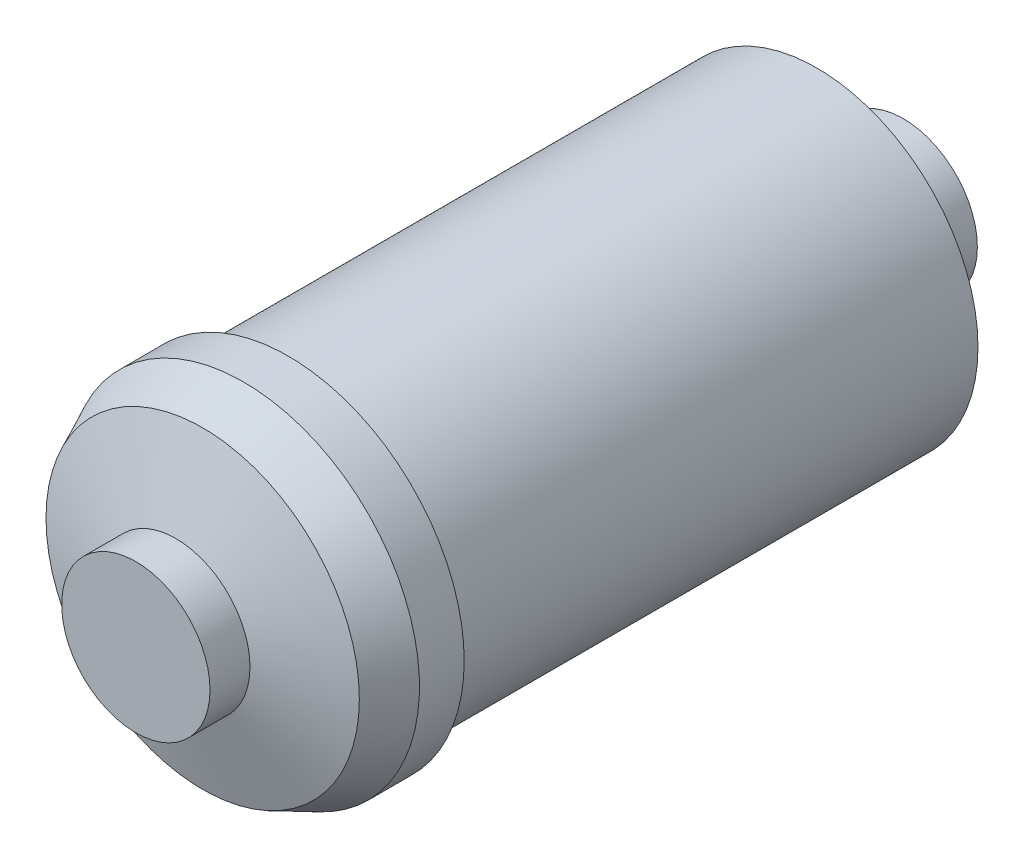
SolidWorks part; units mm, degrees
ref_plane "Front Plane" through (0, 0, 0) normal (0, 0, 1) x (1, 0, 0)
ref_plane "Top Plane" through (0, 0, 0) normal (0, 1, 0) x (1, 0, 0)
ref_plane "Right Plane" through (0, 0, 0) normal (1, 0, 0) x (0, 0, -1)
sketch "Sketch1" plane through (0, 0, 0) normal (0, 0, 1) x (1, 0, 0)
  circle A0 centre (0, 0) radius 14.732
  dimension "D1" = 29.464
extrude "Boss-Extrude1" add sketch "Sketch1" along normal blind 8.255
sketch "Sketch2" plane through (0, 0, 8.255) normal (0, 0, 1) x (1, 0, 0)
  circle A1 centre (0, 0) radius 14.732
  circle A2 centre (0, 0) radius 14.732
  dimension "D1" = 0
ref_plane "Plane1" through (0, 0, 17.145) normal (0, 0, 1) x (1, 0, 0)
sketch "Sketch3" plane through (0, 0, 17.145) normal (0, 0, 1) x (1, 0, 0)
  circle A0 centre (0, 0) radius 32.004
  dimension "D1" = 64.008
loft "Loft1" add profiles "Sketch2", "Sketch3"
sketch "Sketch4" plane through (0, 0, 17.145) normal (0, 0, 1) x (1, 0, 0)
  circle A1 centre (0, 0) radius 32.004
  circle A2 centre (0, 0) radius 32.004
  dimension "D1" = 0
extrude "Boss-Extrude2" add sketch "Sketch4" along normal blind 104.9655
sketch "Sketch5" plane through (0, 0, 122.1105) normal (0, 0, 1) x (1, 0, 0)
  circle A0 centre (0, 0) radius 34.925
  dimension "D1" = 69.85
extrude "Boss-Extrude3" add sketch "Sketch5" along normal blind 8.89
sketch "Sketch6" plane through (0, 0, 131.0005) normal (0, 0, 1) x (1, 0, 0)
  circle A1 centre (0, 0) radius 34.925
  circle A2 centre (0, 0) radius 34.925
  dimension "D1" = 0
ref_plane "Plane2" through (0, 0, 139.1285) normal (0, 0, 1) x (1, 0, 0)
sketch "Sketch7" plane through (0, 0, 139.1285) normal (0, 0, 1) x (1, 0, 0)
  circle A0 centre (0, 0) radius 31.115
  dimension "D1" = 62.23
loft "Loft2" add profiles "Sketch6", "Sketch7"
sketch "Sketch8" plane through (0, 0, 139.1285) normal (0, 0, 1) x (1, 0, 0)
  circle A1 centre (0, 0) radius 31.115
  circle A2 centre (0, 0) radius 31.115
  dimension "D1" = 0
ref_plane "Plane3" through (0, 0, 144.4625) normal (0, 0, 1) x (1, 0, 0)
sketch "Sketch9" plane through (0, 0, 144.4625) normal (0, 0, 1) x (1, 0, 0)
  circle A0 centre (0, 0) radius 14.732
  dimension "D1" = 29.464
loft "Loft3" add profiles "Sketch8", "Sketch9"
sketch "Sketch10" plane through (0, 0, 144.4625) normal (0, 0, 1) x (1, 0, 0)
  circle A1 centre (0, 0) radius 14.732
  circle A2 centre (0, 0) radius 14.732
  dimension "D1" = 0
extrude "Boss-Extrude4" add sketch "Sketch10" along normal blind 7.9375
